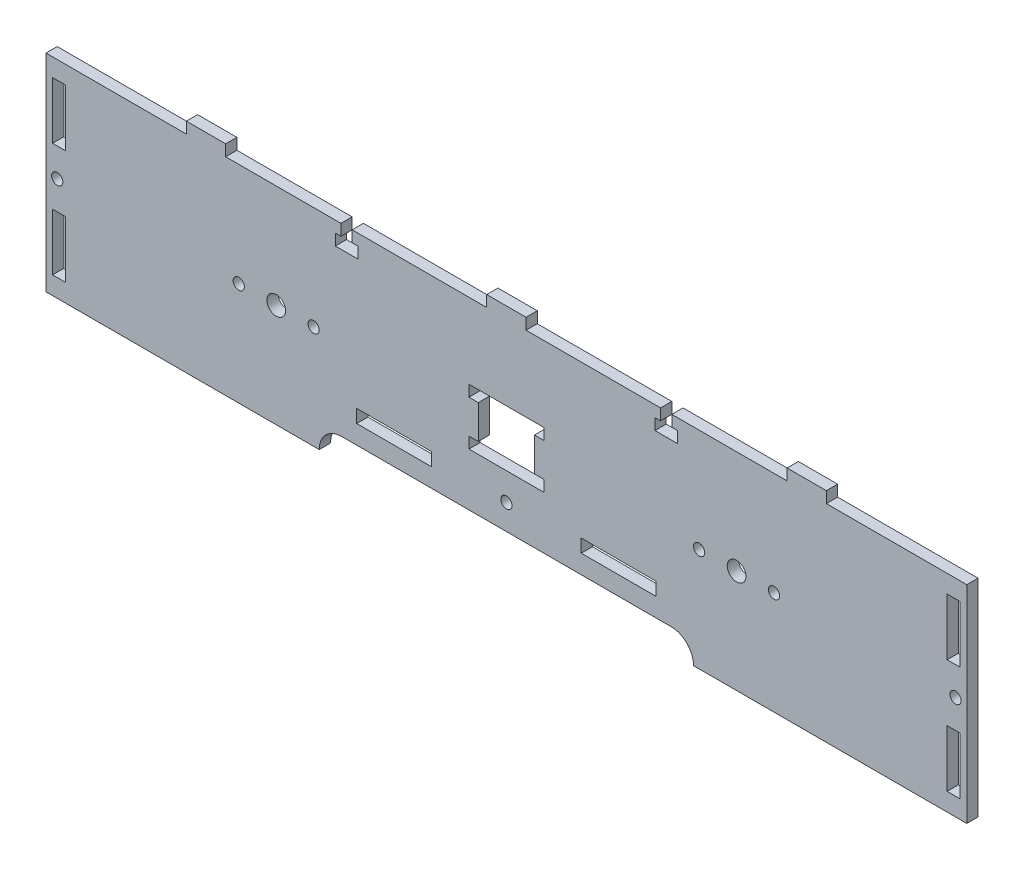
SolidWorks part; units mm, degrees
ref_plane "Alzado" through (0, 0, 0) normal (0, 0, 1) x (1, 0, 0)
ref_plane "Planta" through (0, 0, 0) normal (0, 1, 0) x (1, 0, 0)
ref_plane "Vista lateral" through (0, 0, 0) normal (1, 0, 0) x (0, 0, -1)
sketch "Croquis1" plane through (0, 0, 0) normal (0, 0, 1) x (1, 0, 0)
  line L0 (0, 27.625) -> (0, -21.595) construction
  line L1 (123, -27.625) -> (50, -27.625)
  line L2 (123, -27.625) -> (123, 27.625)
  line L3 (123, 27.625) -> (44.2, 27.625)
  line L4 (-123, -27.625) -> (-123, 27.625)
  line L5 (123, -27.625) -> (-123, 27.625) construction
  line L6 (123, 27.625) -> (-123, -27.625) construction
  line L7 (44, -21.595) -> (-44, -21.595)
  line L8 (-50, -27.595) -> (-50, -27.625)
  line L9 (50, -27.595) -> (50, -27.625)
  line L10 (0, 0) -> (0, 7.5) construction
  line L11 (-10, 7.5) -> (10, 7.5)
  line L12 (-10, 7.5) -> (-10, 4.5)
  line L13 (-10, 4.5) -> (-7.5, 4.5)
  line L14 (-7.5, 4.5) -> (-7.5, -4.5)
  line L15 (0, 0) -> (-123, 0) construction
  line L16 (10, 7.5) -> (10, 4.5)
  line L17 (10, 4.5) -> (7.5, 4.5)
  line L18 (7.5, 4.5) -> (7.5, -4.5)
  line L19 (10, -7.5) -> (10, -4.5)
  line L20 (10, -4.5) -> (7.5, -4.5)
  line L21 (123, -27.625) -> (50, -27.625)
  line L22 (123, 27.625) -> (44.2, 27.625)
  line L23 (-10, -7.5) -> (10, -7.5)
  line L24 (-10, -7.5) -> (-10, -4.5)
  line L25 (-10, -4.5) -> (-7.5, -4.5)
  line L26 (-50, -27.625) -> (-123, -27.625)
  line L27 (-50, -27.625) -> (-123, -27.625)
  line L28 (0, 0) -> (123, 0) construction
  line L29 (40, -16.595) -> (20, -16.595)
  line L30 (40, -16.595) -> (40, -13.095)
  line L31 (40, -13.095) -> (20, -13.095)
  line L32 (20, -16.595) -> (20, -13.095)
  line L33 (40, -16.595) -> (20, -13.095) construction
  line L34 (40, -13.095) -> (20, -16.595) construction
  line L35 (117.75, 22.825) -> (121.25, 22.825)
  line L36 (117.75, 22.825) -> (117.75, 7.625)
  line L37 (117.75, 7.625) -> (121.25, 7.625)
  line L38 (121.25, 22.825) -> (121.25, 7.625)
  line L39 (117.75, 22.825) -> (121.25, 7.625) construction
  line L40 (117.75, 7.625) -> (121.25, 22.825) construction
  line L41 (117.75, -7.625) -> (121.25, -7.625)
  line L42 (117.75, -7.625) -> (117.75, -22.825)
  line L43 (117.75, -22.825) -> (121.25, -22.825)
  line L44 (121.25, -7.625) -> (121.25, -22.825)
  line L45 (117.75, -7.625) -> (121.25, -22.825) construction
  line L46 (117.75, -22.825) -> (121.25, -7.625) construction
  line L47 (61.5, 0) -> (61.5, 27.625) construction
  line L48 (44.2, 27.625) -> (44.2, 24.625)
  line L49 (44.2, 24.625) -> (45.7, 24.625)
  line L50 (45.7, 24.625) -> (45.7, 21.625)
  line L51 (45.7, 21.625) -> (39.7, 21.625)
  line L52 (39.7, 24.625) -> (39.7, 21.625)
  line L53 (41.2, 24.625) -> (39.7, 24.625)
  line L54 (41.2, 27.625) -> (41.2, 24.625)
  line L55 (42.7, 21.625) -> (42.7, 27.625) construction
  line L56 (41.2, 27.625) -> (-41.2, 27.625)
  line L57 (41.2, 27.625) -> (-41.2, 27.625)
  line L58 (-117.75, 7.625) -> (-121.25, 7.625)
  line L59 (-121.25, 22.825) -> (-121.25, 7.625)
  line L60 (-117.75, 22.825) -> (-121.25, 22.825)
  line L61 (-117.75, 22.825) -> (-117.75, 7.625)
  line L62 (-117.75, -22.825) -> (-121.25, -22.825)
  line L63 (-121.25, -7.625) -> (-121.25, -22.825)
  line L64 (-117.75, -7.625) -> (-121.25, -7.625)
  line L65 (-117.75, -7.625) -> (-117.75, -22.825)
  line L66 (-40, -13.095) -> (-20, -13.095)
  line L67 (-20, -16.595) -> (-20, -13.095)
  line L68 (-40, -16.595) -> (-20, -16.595)
  line L69 (-40, -16.595) -> (-40, -13.095)
  line L70 (-44.2, 27.625) -> (-44.2, 24.625)
  line L71 (-45.7, 24.625) -> (-45.7, 21.625)
  line L72 (-45.7, 21.625) -> (-39.7, 21.625)
  line L73 (-39.7, 24.625) -> (-39.7, 21.625)
  line L74 (-41.2, 24.625) -> (-39.7, 24.625)
  line L75 (-41.2, 27.625) -> (-41.2, 24.625)
  line L76 (-44.2, 27.625) -> (-123, 27.625)
  line L77 (-44.2, 27.625) -> (-123, 27.625)
  line L78 (-41.2, 24.625) -> (-39.7, 24.625)
  line L79 (-45.7, 24.625) -> (-44.2, 24.625)
  arc A0 (44, -21.595) -> (50, -27.595) centre (44, -27.595) cw
  arc A1 (-44, -21.595) -> (-50, -27.595) centre (-44, -27.595) ccw
  circle A2 centre (61.5, 0) radius 2.5
  circle A3 centre (71.5, 0) radius 1.5
  circle A4 centre (51.5, 0) radius 1.5
  circle A5 centre (-71.5, 0) radius 1.5
  circle A6 centre (-61.5, 0) radius 2.5
  circle A7 centre (-51.5, 0) radius 1.5
  point P0 (0, 0)
  point P11 (0, -21.595)
  point P15 (50, -21.595)
  point P18 (-50, -21.595)
  point P24 (0, 7.5)
  point P25 (119.5, 15.225)
  point P27 (30, -14.845)
  point P33 (7.5, 0)
  point P38 (-7.5, 0)
  point P47 (119.5, -15.225)
  dimension "D5" = 6
  dimension "D19" = 5
  dimension "D20" = 3
  dimension "D1" = 55.25
  dimension "D2" = 246
  dimension "D3" = 49.22
  dimension "D4" = 100
  dimension "D6" = 7.5
  dimension "D7" = 20
  dimension "D8" = 7.5
  dimension "D9" = 3
  dimension "D10" = 20
  dimension "D11" = 5
  dimension "D12" = 3.5
  dimension "D13" = 20
  dimension "D14" = 3.5
  dimension "D15" = 1.75
  dimension "D16" = 15.2
  dimension "D17" = 4.8
  dimension "D18" = 4.8
  dimension "D21" = 10
  dimension "D22" = 78.8
  dimension "D23" = 6
  dimension "D24" = 3
  dimension "D25" = 3
  dimension "D26" = 1.5
extrude "Saliente-Extruir1" add sketch "Croquis1" along normal blind 3 contours A1 L7 A0 L9 L1 L2 L3 L48 L49 L50 L51 L52 L53 L54 L56 L75 L74 L73 L72 L71 L79 L70 L76 L4 L26 L8 A7 A5 L68 L69 L66 L67 L64 L65 L62 L63 L60 L61 L58 L59 L41 L44 L43 L42
sketch "Croquis2" plane through (0, 27.625, 0) normal (0, 1, 0) x (1, 0, 0)
  line L0 (-5.25, -3) -> (5.25, -3) construction
  line L1 (-5.25, 0.05) -> (-5.25, -3.45) construction
  line L2 (41.2, -3) -> (-41.2, -3) construction
  line L3 (5.25, -3.45) -> (5.25, 0.05) construction
  line L4 (0, -3) -> (0, 0) construction
  line L5 (75, -3) -> (85.5, -3) construction
  line L6 (-5.25, 0) -> (5.25, 0)
  line L7 (-5.25, 0) -> (-5.25, -3)
  line L8 (-5.25, -3) -> (5.25, -3)
  line L9 (5.25, 0) -> (5.25, -3)
  line L10 (-5.25, 0) -> (5.25, -3) construction
  line L11 (-5.25, -3) -> (5.25, 0) construction
  line L12 (123, -3) -> (44.2, -3) construction
  line L13 (75, 0.05) -> (75, -3.45) construction
  line L14 (85.5, -3.45) -> (85.5, 0.05) construction
  line L15 (80.25, -3) -> (80.25, 0) construction
  line L16 (123, 0) -> (44.2, 0) construction
  line L17 (-85.5, -3) -> (-75, -3) construction
  line L18 (75, 0) -> (85.5, 0)
  line L19 (75, 0) -> (75, -3)
  line L20 (75, -3) -> (85.5, -3)
  line L21 (85.5, 0) -> (85.5, -3)
  line L22 (75, 0) -> (85.5, -3) construction
  line L23 (75, -3) -> (85.5, 0) construction
  line L24 (-85.5, 0.05) -> (-85.5, -3.45) construction
  line L25 (-44.2, -3) -> (-123, -3) construction
  line L26 (-75, -3.45) -> (-75, 0.05) construction
  line L27 (-80.25, -3) -> (-80.25, 0) construction
  line L28 (-44.2, 0) -> (-123, 0) construction
  line L30 (-85.5, 0) -> (-75, 0)
  line L31 (-85.5, 0) -> (-85.5, -3)
  line L32 (-85.5, -3) -> (-75, -3)
  line L33 (-75, 0) -> (-75, -3)
  line L34 (-85.5, 0) -> (-75, -3) construction
  line L35 (-85.5, -3) -> (-75, 0) construction
  point P11 (0, -1.5)
  point P26 (80.25, -1.5)
  point P41 (-80.25, -1.5)
extrude "Saliente-Extruir2" add sketch "Croquis2" along normal up to surface (3 mm away)
sketch "Croquis3" plane through (0, 0, 3) normal (0, 0, 1) x (1, 0, 0)
  line L0 (-123, 0) -> (-110.686, 0) construction
  line L1 (-123, -27.625) -> (-123, 27.625) construction
  line L2 (0, 0) -> (0, -21.595) construction
  line L3 (44, -21.595) -> (-44, -21.595) construction
  circle A0 centre (-120, 0) radius 1.5
  circle A1 centre (120, 0) radius 1.5
  dimension "D1" = 3
  dimension "D2" = 3
extrude "Cortar-Extruir1" cut sketch "Croquis3" against normal blind 3
sketch "Croquis4" plane through (0, 0, 3) normal (0, 0, 1) x (1, 0, 0)
  line L0 (-20, -16.595) -> (-20, -13.095) construction
  circle A0 centre (0, -14.845) radius 1.5
  point P5 (-20, -14.845)
  dimension "D1" = 3
extrude "Cortar-Extruir2" cut sketch "Croquis4" against normal blind 3
